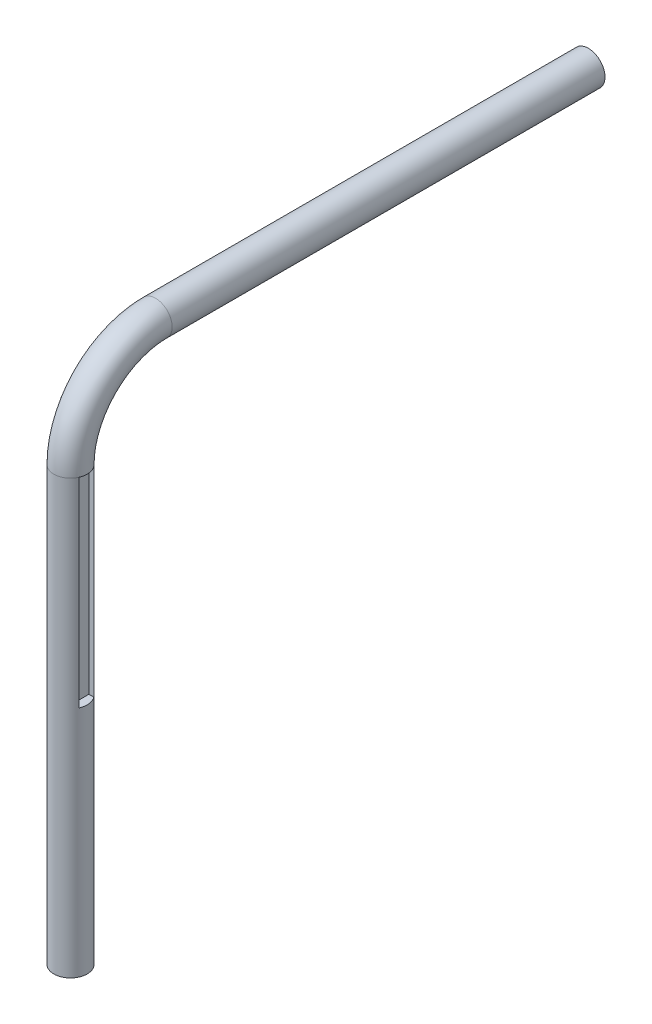
SolidWorks part; units mm, degrees
material "Cast Carbon Steel"
ref_plane "Front Plane" through (0, 0, 0) normal (0, 0, 1) x (1, 0, 0)
ref_plane "Top Plane" through (0, 0, 0) normal (0, 1, 0) x (1, 0, 0)
ref_plane "Right Plane" through (0, 0, 0) normal (1, 0, 0) x (0, 0, -1)
sketch "Sketch2" plane through (0, 0, 0) normal (1, 0, 0) x (0, 0, -1)
  arc A0 (-64.8338, 0) -> (0, 64.8338) centre (0, 0) cw
sketch "Sketch3" plane through (0, 0, 0) normal (0, 1, 0) x (1, 0, 0)
  circle A0 centre (0, -64.8338) radius 12.7
  dimension "D1" = 25.4
sweep "Sweep1" add profiles "Sketch3" path "Sketch2"
ref_plane "Plane1" through (0, 0, 0) normal (0, -1, 0) x (-1, 0, 0)
ref_plane "Plane2" through (0, 0, 0) normal (0, 0, -1) x (-1, 0, 0)
sketch "Sketch4" plane through (0, 0, 0) normal (0, -1, 0) x (-1, 0, 0)
  circle A0 centre (0, -64.8338) radius 12.7
extrude "Boss-Extrude3" add sketch "Sketch4" along normal blind 330.2
sketch "Sketch5" plane through (0, 0, 0) normal (0, 0, -1) x (-1, 0, 0)
  circle A0 centre (0, 64.8338) radius 12.7
extrude "Boss-Extrude4" add sketch "Sketch5" along normal blind 330.2
ref_plane "Plane3" through (-12.7, 0, 0) normal (-1, 0, 0) x (0, 0, 1)
ref_plane "Plane4" through (12.7, 0, 0) normal (1, 0, 0) x (0, 0, -1)
sketch "Sketch7" plane through (12.7, 0, 0) normal (1, 0, 0) x (0, 0, -1)
  line L0 (0, -55) -> (0, 55) construction
  line L1 (-69.85, 0) -> (-57.15, 0)
  line L2 (-69.85, 0) -> (-69.85, -152.4)
  line L3 (-69.85, -152.4) -> (-57.15, -152.4)
  line L4 (-57.15, 0) -> (-57.15, -152.4)
  line L5 (-52.1338, 0) -> (-77.5338, 0) construction
  point P9 (-63.5, -152.4)
  dimension "D1" = 12.7
  dimension "D2" = 152.4
  dimension "D3" = 57.15
  dimension "D4" = 63.5
extrude "Cut-Extrude2" cut sketch "Sketch7" against normal blind 6.35
